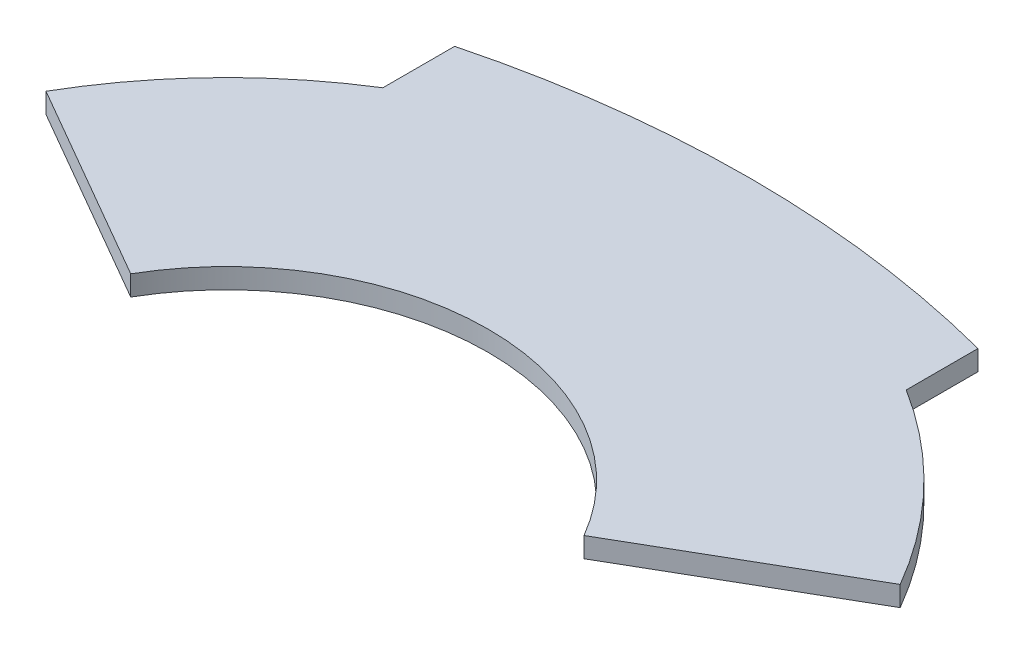
SolidWorks part; units mm, degrees
ref_plane "前视基准面" through (0, 0, 0) normal (0, 0, 1) x (1, 0, 0)
ref_plane "上视基准面" through (0, 0, 0) normal (0, 1, 0) x (1, 0, 0)
ref_plane "右视基准面" through (0, 0, 0) normal (1, 0, 0) x (0, 0, -1)
other "Configuration Table"
sketch "草图1" plane through (0, 0, 0) normal (0, 1, 0) x (1, 0, 0)
  line L0 (-26, 96.5609) -> (26, 96.5609) construction
  line L1 (-26, 99.6644) -> (-26, 96.5609)
  line L3 (0, 0) -> (0, 125.1378) construction
  line L4 (-22.5167, 64) -> (-42.4352, 75.5)
  line L5 (22.5167, 64) -> (42.4352, 75.5)
  line L6 (-26, 96.5609) -> (-26, 92.5331)
  line L7 (26, 96.5609) -> (26, 92.5331)
  line L9 (26, 99.6644) -> (26, 96.5609)
  circle A0 centre (0, 0) radius 100 construction
  circle A1 centre (0, 0) radius 103 construction
  arc A2 (-26, 96.5609) -> (26, 96.5609) centre (0, 0) cw construction
  arc A3 (-26, 99.6644) -> (26, 99.6644) centre (0, 0) cw
  circle A4 centre (0, 51) radius 49 construction
  arc A5 (-42.4352, 75.5) -> (-26, 92.5331) centre (0, 51) cw
  arc A6 (42.4352, 75.5) -> (26, 92.5331) centre (0, 51) ccw
  arc A7 (-22.5167, 64) -> (22.5167, 64) centre (0, 51) cw
  dimension "D1" = 200
  dimension "D2" = 206
  dimension "D4" = 98
  dimension "D7" = 26
  dimension "D3" = 52
  dimension "D5" = 60
  dimension "D6" = 60
  dimension "D8" = 23
  dimension "D9" = 23
extrude "凸台-拉伸1" add sketch "草图1" along normal blind 2
